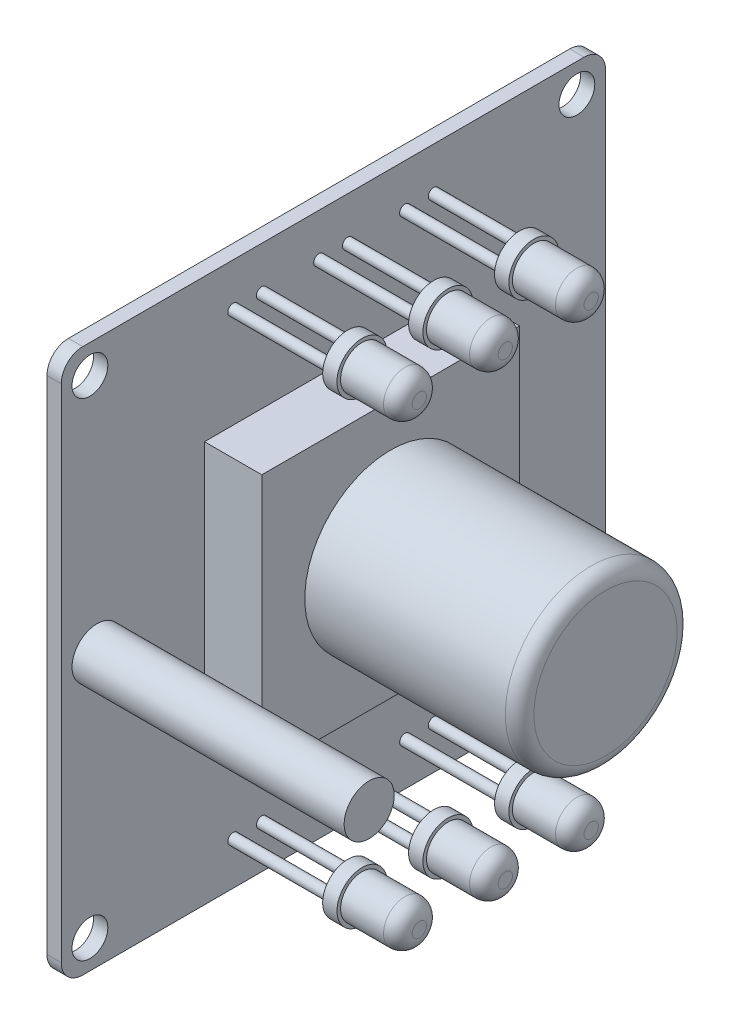
SolidWorks part; units mm, degrees
ref_plane "Front Plane" through (0, 0, 0) normal (1, 0, 0) x (0, 1, 0)
ref_plane "Top Plane" through (0, 0, 0) normal (0, 0, 1) x (0, 1, 0)
ref_plane "Right Plane" through (0, 0, 0) normal (0, 1, 0) x (-1, 0, 0)
sketch "Sketch1" plane through (0, 0, 0) normal (1, 0, 0) x (0, 1, 0)
  line L1 (19, -19) -> (-19, -19)
  line L2 (19, -19) -> (19, 19)
  line L3 (19, 19) -> (-19, 19)
  line L4 (-19, -19) -> (-19, 19)
  line L5 (19, -19) -> (-19, 19) construction
  line L6 (19, 19) -> (-19, -19) construction
  circle A0 centre (-17, 17) radius 1.25
  circle A1 centre (17, 17) radius 1.25
  circle A3 centre (-17, -17) radius 1.25
  circle A4 centre (17, -17) radius 1.25
  point P0 (0, 0)
  dimension "D2" = 2.5
  dimension "D1" = 38
  dimension "D3" = 17
  dimension "D4" = 17
  dimension "D5" = 17
  dimension "D6" = 17
extrude "Boss-Extrude1" add sketch "Sketch1" along normal blind 1
fillet "Fillet1" radius 1.5 4 edges at (0.5, 19, 19) (0.5, -19, -19) (0.5, 19, -19) (0.5, -19, 19)
sketch "Sketch2" plane through (0, 0, 0) normal (1, 0, 0) x (0, 1, 0)
  line L0 (0, 0) -> (0, 19) construction
  line L1 (17.5, 19) -> (-17.5, 19) construction
  circle A0 centre (-16, 7) radius 0.375
  circle A1 centre (-16, 5) radius 0.375
  circle A2 centre (-16, 1) radius 0.375
  circle A3 centre (-16, -1) radius 0.375
  circle A4 centre (-16, -5) radius 0.375
  circle A5 centre (-16, -7) radius 0.375
  circle A6 centre (16, -7) radius 0.375
  circle A7 centre (16, -5) radius 0.375
  circle A8 centre (16, -1) radius 0.375
  circle A9 centre (16, 1) radius 0.375
  circle A10 centre (16, 5) radius 0.375
  circle A11 centre (16, 7) radius 0.375
  dimension "D4" = 0.75
  dimension "D2" = 7
  dimension "D3" = 16
  dimension "D5" = 2
  dimension "D6" = 1
  dimension "D7" = 2
  dimension "D8" = 2
  dimension "D9" = 7
  dimension "D10" = 16
  dimension "D11" = 16
  dimension "D12" = 16
  dimension "D13" = 16
  dimension "D14" = 16
extrude "Boss-Extrude2" add sketch "Sketch2" along normal blind 8
ref_plane "Plane1" through (8, 0, 0) normal (1, 0, 0) x (0, 1, 0)
sketch "Sketch4" plane through (8, 0, 0) normal (1, 0, 0) x (0, 1, 0)
  line L0 (-16, 7) -> (-16, -7) construction
  line L1 (0, 0) -> (0, 19) construction
  line L2 (17.5, 19) -> (-17.5, 19) construction
  circle A0 centre (-16, 6) radius 1.75
  circle A1 centre (-16, 0) radius 1.75
  circle A2 centre (-16, -6) radius 1.75
  circle A3 centre (16, -6) radius 1.75
  circle A4 centre (16, 0) radius 1.75
  circle A5 centre (16, 6) radius 1.75
  dimension "D1" = 3.5
  dimension "D2" = 6
  dimension "D3" = 6
extrude "Boss-Extrude3" add sketch "Sketch4" along normal blind 1
sketch "Sketch5" plane through (8, 0, 0) normal (1, 0, 0) x (0, 1, 0)
  line L0 (-16, 6) -> (-16, 0) construction
  line L1 (-16, 0) -> (-16, -6) construction
  line L2 (0, 0) -> (0, 19) construction
  line L3 (17.5, 19) -> (-17.5, 19) construction
  circle A0 centre (-16, 6) radius 1.5
  circle A1 centre (-16, 0) radius 1.5
  circle A2 centre (-16, -6) radius 1.5
  circle A3 centre (16, -6) radius 1.5
  circle A4 centre (16, 0) radius 1.5
  circle A5 centre (16, 6) radius 1.5
  dimension "D1" = 3
extrude "Boss-Extrude4" add sketch "Sketch5" along normal blind 5
fillet "Fillet2" radius 1 6 edges at (13, 16, -4.5) (13, 16, 1.5) (13, 16, 7.5) (13, -16, -7.5) (13, -16, -1.5) (13, -16, 4.5)
sketch "Sketch6" plane through (0, 0, 0) normal (1, 0, 0) x (0, 1, 0)
  line L1 (9, -9) -> (-9, -9)
  line L2 (9, -9) -> (9, 9)
  line L3 (9, 9) -> (-9, 9)
  line L4 (-9, -9) -> (-9, 9)
  line L5 (9, -9) -> (-9, 9) construction
  line L6 (9, 9) -> (-9, -9) construction
  point P0 (0, 0)
  dimension "D2" = 18
extrude "Boss-Extrude5" add sketch "Sketch6" along normal blind 5
sketch "Sketch7" plane through (0, 0, 0) normal (1, 0, 0) x (0, 1, 0)
  circle A0 centre (0, 0) radius 6
  dimension "D1" = 12
extrude "Boss-Extrude6" add sketch "Sketch7" along normal blind 20
fillet "Fillet3" radius 1 1 edges at (20, 0, -6)
sketch "Sketch8" plane through (0, 0, 0) normal (1, 0, 0) x (0, 1, 0)
  line L0 (0, -11) -> (0, 11) construction
  circle A0 centre (0, 16.5) radius 1.75
  point P2 (0, 16.5)
  point P4 (0, 0)
  dimension "D1" = 3.5
  dimension "D2" = 16.5
extrude "Boss-Extrude7" add sketch "Sketch8" along normal blind 20
